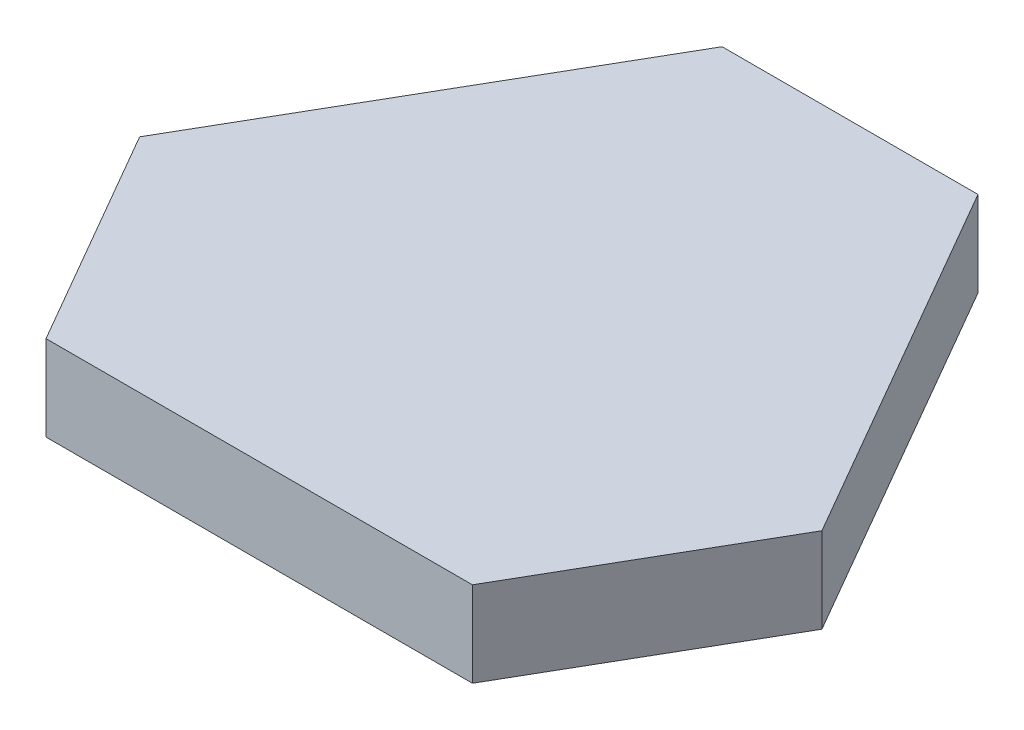
SolidWorks part; units mm, degrees
ref_plane "前视基准面" through (0, 0, 0) normal (0, 0, 1) x (1, 0, 0)
ref_plane "上视基准面" through (0, 0, 0) normal (0, 1, 0) x (1, 0, 0)
ref_plane "右视基准面" through (0, 0, 0) normal (1, 0, 0) x (0, 0, -1)
sketch "草图1" plane through (0, 0, 0) normal (0, 1, 0) x (1, 0, 0)
  line L0 (-15, 37.5278) -> (15, 37.5278)
  line L10 (15, 37.5278) -> (40, -5.7735)
  line L11 (40, -5.7735) -> (25, -31.7543)
  line L12 (25, -31.7543) -> (-25, -31.7543)
  line L13 (-25, -31.7543) -> (-40, -5.7735)
  line L14 (-40, -5.7735) -> (-15, 37.5278)
  line L15 (27.5, 15.8771) -> (-32.5, -18.7639) construction
  line L16 (-27.5, 15.8771) -> (32.5, -18.7639) construction
  point P8 (-17.518, -8.4461)
  point P11 (0, 0)
  point P12 (0, 0)
  dimension "D1" = 120
  dimension "D2" = 120
  dimension "D3" = 30
  dimension "D4" = 50
extrude "凸台-拉伸1" add sketch "草图1" along normal blind 10
